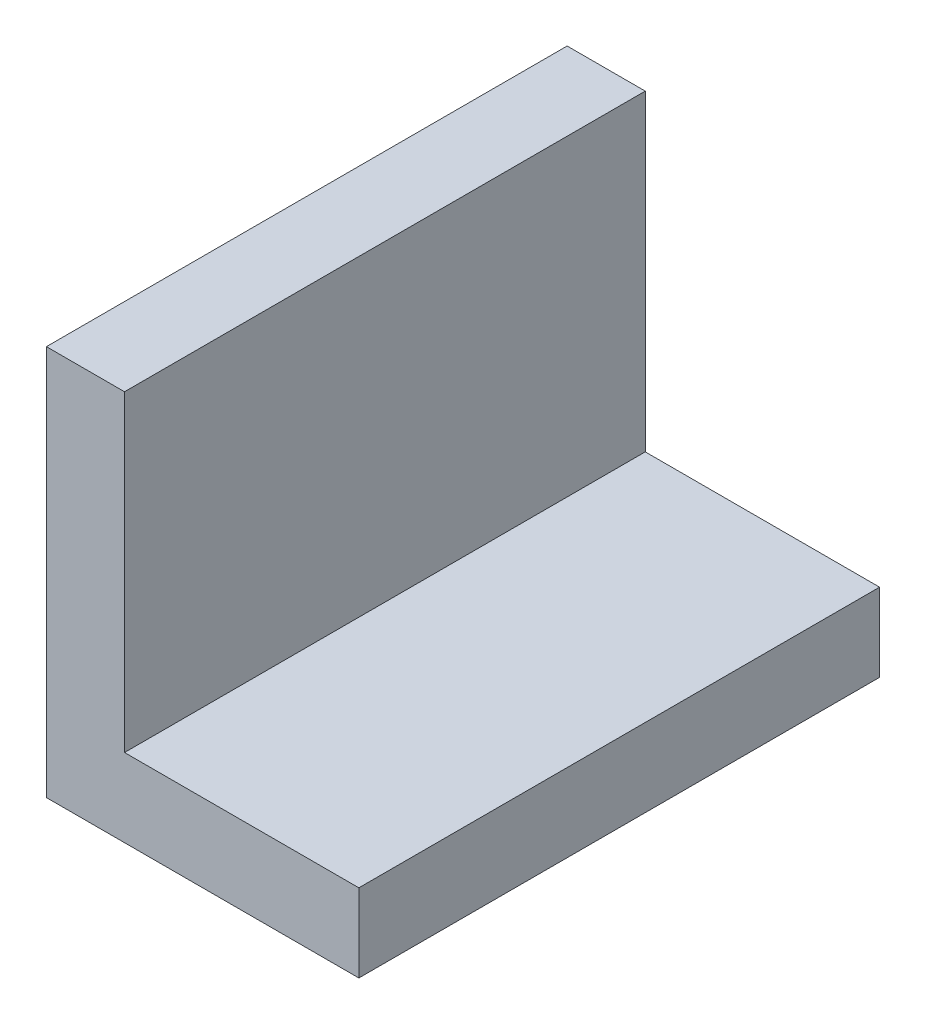
SolidWorks part; units mm, degrees
ref_plane "Front Plane" through (0, 0, 0) normal (0, 0, 1) x (1, 0, 0)
ref_plane "Top Plane" through (0, 0, 0) normal (0, 1, 0) x (1, 0, 0)
ref_plane "Right Plane" through (0, 0, 0) normal (1, 0, 0) x (0, 0, -1)
sketch "Sketch1" plane through (0, 0, 0) normal (0, 0, 1) x (1, 0, 0)
  line L0 (0, 0) -> (0, 75)
  line L1 (0, 75) -> (15, 75)
  line L2 (15, 75) -> (15, 15)
  line L3 (15, 15) -> (60, 15)
  line L4 (60, 15) -> (60, 0)
  line L5 (60, 0) -> (0, 0)
  dimension "D1" = 15
  dimension "D2" = 75
  dimension "D3" = 60
  dimension "D4" = 15
extrude "Boss-Extrude1" add sketch "Sketch1" along normal blind 100
